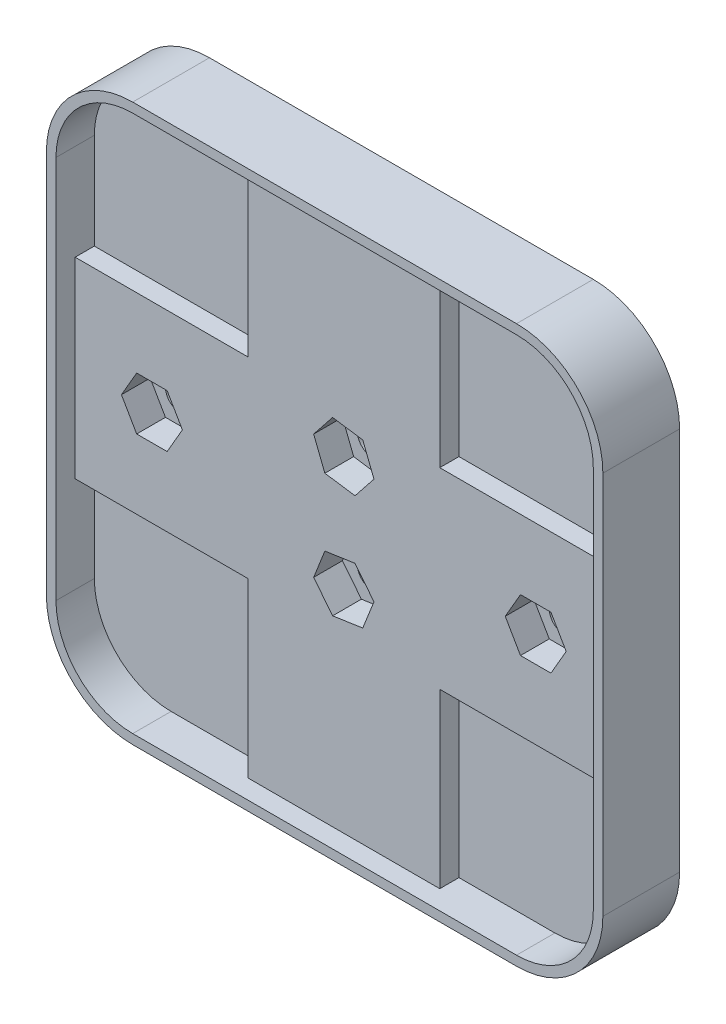
SolidWorks part; units mm, degrees
ref_plane "Front" through (0, 0, 0) normal (0, 0, 1) x (1, 0, 0)
ref_plane "Top" through (0, 0, 0) normal (0, 1, 0) x (1, 0, 0)
ref_plane "Right" through (0, 0, 0) normal (1, 0, 0) x (0, 0, -1)
sketch "草图1" plane through (0, 0, 0) normal (0, 0, 1) x (1, 0, 0)
  line L0 (-15.4063, 105.3183) -> (-15.4063, -125.7754) construction
  line L1 (-238.6458, 35.5371) -> (237.4375, 35.5371) construction
  line L2 (-35.4063, 64.5371) -> (4.5937, 64.5371)
  line L3 (13.5937, 55.5371) -> (13.5937, 15.5371)
  line L4 (4.5937, 6.5371) -> (-35.4063, 6.5371)
  line L5 (-44.4063, 15.5371) -> (-44.4063, 55.5371)
  arc A0 (13.5937, 55.5371) -> (4.5937, 64.5371) centre (4.5937, 55.5371) ccw
  arc A1 (4.5937, 6.5371) -> (13.5937, 15.5371) centre (4.5937, 15.5371) ccw
  arc A2 (-35.4063, 6.5371) -> (-44.4063, 15.5371) centre (-35.4063, 15.5371) cw
  arc A3 (-44.4063, 55.5371) -> (-35.4063, 64.5371) centre (-35.4063, 55.5371) cw
  point P16 (-44.4063, 64.5371)
  dimension "D5" = 9
  dimension "D6" = 9
  dimension "D1" = 29
  dimension "D2" = 58
  dimension "D3" = 58
  dimension "D4" = 29
extrude "凸台-拉伸1" add sketch "草图1" against normal blind 4
sketch "草图2" plane through (0, 0, 0) normal (0, 0, 1) x (1, 0, 0)
  line L0 (13.5937, 15.5371) -> (13.5937, 55.5371) construction
  line L1 (-35.4063, 6.5371) -> (4.5937, 6.5371) construction
  line L2 (-44.4063, 55.5371) -> (-44.4063, 15.5371) construction
  line L3 (4.5937, 64.5371) -> (-35.4063, 64.5371) construction
  line L4 (13.5937, 15.5371) -> (13.5937, 55.5371)
  line L5 (-35.4063, 6.5371) -> (4.5937, 6.5371)
  line L6 (-44.4063, 55.5371) -> (-44.4063, 15.5371)
  line L7 (4.5937, 64.5371) -> (-35.4063, 64.5371)
  line L8 (-35.4063, 63.5371) -> (-25.4063, 63.5371)
  line L9 (12.5937, 55.5371) -> (12.5937, 45.5371)
  line L10 (-43.4063, 55.5371) -> (-43.4063, 45.5371)
  line L11 (-35.4063, 7.5371) -> (-25.4063, 7.5371)
  line L12 (-25.4063, 63.5371) -> (-25.4063, 45.5371)
  line L13 (-15.4063, 63.5371) -> (-15.4063, 7.5371) construction
  line L14 (-44.4063, 35.5371) -> (13.5937, 35.5371) construction
  line L15 (-5.4063, 63.5371) -> (-5.4063, 45.5371)
  line L16 (-25.4063, 45.5371) -> (-43.4063, 45.5371)
  line L17 (-5.4063, 45.5371) -> (12.5937, 45.5371)
  line L18 (-5.4063, 25.5371) -> (12.5937, 25.5371)
  line L19 (-25.4063, 25.5371) -> (-43.4063, 25.5371)
  line L20 (-25.4063, 25.5371) -> (-25.4063, 7.5371)
  line L21 (-5.4063, 25.5371) -> (-5.4063, 7.5371)
  line L22 (-43.4063, 25.5371) -> (-43.4063, 15.5371)
  line L23 (-5.4063, 7.5371) -> (4.5937, 7.5371)
  line L24 (12.5937, 25.5371) -> (12.5937, 15.5371)
  line L25 (-5.4063, 63.5371) -> (4.5937, 63.5371)
  arc A0 (13.5937, 55.5371) -> (4.5937, 64.5371) centre (4.5937, 55.5371) ccw construction
  arc A1 (4.5937, 6.5371) -> (13.5937, 15.5371) centre (4.5937, 15.5371) ccw construction
  arc A2 (-44.4063, 15.5371) -> (-35.4063, 6.5371) centre (-35.4063, 15.5371) ccw construction
  arc A3 (-35.4063, 64.5371) -> (-44.4063, 55.5371) centre (-35.4063, 55.5371) ccw construction
  arc A4 (13.5937, 55.5371) -> (4.5937, 64.5371) centre (4.5937, 55.5371) ccw
  arc A5 (4.5937, 6.5371) -> (13.5937, 15.5371) centre (4.5937, 15.5371) ccw
  arc A6 (-44.4063, 15.5371) -> (-35.4063, 6.5371) centre (-35.4063, 15.5371) ccw
  arc A7 (-35.4063, 64.5371) -> (-44.4063, 55.5371) centre (-35.4063, 55.5371) ccw
  arc A8 (-35.4063, 7.5371) -> (-43.4063, 15.5371) centre (-35.4063, 15.5371) cw
  arc A9 (4.5937, 7.5371) -> (12.5937, 15.5371) centre (4.5937, 15.5371) ccw
  arc A10 (12.5937, 55.5371) -> (4.5937, 63.5371) centre (4.5937, 55.5371) ccw
  arc A11 (-43.4063, 55.5371) -> (-35.4063, 63.5371) centre (-35.4063, 55.5371) cw
  dimension "D5" = 8
  dimension "D1" = 1
  dimension "D2" = 1
  dimension "D3" = 1
  dimension "D4" = 1
  dimension "D6" = 10
  dimension "D7" = 10
  dimension "D8" = 10
extrude "凸台-拉伸2" add sketch "草图2" along normal blind 2
sketch "草图3" plane through (0, 0, 2) normal (0, 0, 1) x (1, 0, 0)
  line L0 (-43.4063, 55.5371) -> (-43.4063, 45.5371) construction
  line L1 (-43.4063, 25.5371) -> (-43.4063, 15.5371) construction
  line L2 (-35.4063, 7.5371) -> (-25.4063, 7.5371) construction
  line L3 (-5.4063, 7.5371) -> (4.5937, 7.5371) construction
  line L4 (12.5937, 15.5371) -> (12.5937, 25.5371) construction
  line L5 (12.5937, 45.5371) -> (12.5937, 55.5371) construction
  line L6 (4.5937, 63.5371) -> (-5.4063, 63.5371) construction
  line L7 (-25.4063, 63.5371) -> (-35.4063, 63.5371) construction
  line L8 (13.5937, 15.5371) -> (13.5937, 55.5371) construction
  line L9 (-35.4063, 6.5371) -> (4.5937, 6.5371) construction
  line L10 (-44.4063, 55.5371) -> (-44.4063, 15.5371) construction
  line L11 (4.5937, 64.5371) -> (-35.4063, 64.5371) construction
  line L12 (-43.4063, 55.5371) -> (-43.4063, 45.5371)
  line L13 (-43.4063, 25.5371) -> (-43.4063, 15.5371)
  line L14 (-35.4063, 7.5371) -> (-25.4063, 7.5371)
  line L15 (-5.4063, 7.5371) -> (4.5937, 7.5371)
  line L16 (12.5937, 15.5371) -> (12.5937, 25.5371)
  line L17 (12.5937, 45.5371) -> (12.5937, 55.5371)
  line L18 (4.5937, 63.5371) -> (-5.4063, 63.5371)
  line L19 (-25.4063, 63.5371) -> (-35.4063, 63.5371)
  line L20 (13.5937, 15.5371) -> (13.5937, 55.5371)
  line L21 (-35.4063, 6.5371) -> (4.5937, 6.5371)
  line L22 (-44.4063, 55.5371) -> (-44.4063, 15.5371)
  line L23 (4.5937, 64.5371) -> (-35.4063, 64.5371)
  line L24 (-25.4063, 63.5371) -> (-5.4063, 63.5371)
  line L25 (12.5937, 45.5371) -> (12.5937, 25.5371)
  line L26 (-5.4063, 7.5371) -> (-25.4063, 7.5371)
  line L27 (-43.4063, 45.5371) -> (-43.4063, 25.5371)
  arc A0 (-43.4063, 15.5371) -> (-35.4063, 7.5371) centre (-35.4063, 15.5371) ccw construction
  arc A1 (4.5937, 7.5371) -> (12.5937, 15.5371) centre (4.5937, 15.5371) ccw construction
  arc A2 (12.5937, 55.5371) -> (4.5937, 63.5371) centre (4.5937, 55.5371) ccw construction
  arc A3 (-35.4063, 63.5371) -> (-43.4063, 55.5371) centre (-35.4063, 55.5371) ccw construction
  arc A4 (13.5937, 55.5371) -> (4.5937, 64.5371) centre (4.5937, 55.5371) ccw construction
  arc A5 (4.5937, 6.5371) -> (13.5937, 15.5371) centre (4.5937, 15.5371) ccw construction
  arc A6 (-44.4063, 15.5371) -> (-35.4063, 6.5371) centre (-35.4063, 15.5371) ccw construction
  arc A7 (-35.4063, 64.5371) -> (-44.4063, 55.5371) centre (-35.4063, 55.5371) ccw construction
  arc A8 (-43.4063, 15.5371) -> (-35.4063, 7.5371) centre (-35.4063, 15.5371) ccw
  arc A9 (4.5937, 7.5371) -> (12.5937, 15.5371) centre (4.5937, 15.5371) ccw
  arc A10 (12.5937, 55.5371) -> (4.5937, 63.5371) centre (4.5937, 55.5371) ccw
  arc A11 (-35.4063, 63.5371) -> (-43.4063, 55.5371) centre (-35.4063, 55.5371) ccw
  arc A12 (13.5937, 55.5371) -> (4.5937, 64.5371) centre (4.5937, 55.5371) ccw
  arc A13 (4.5937, 6.5371) -> (13.5937, 15.5371) centre (4.5937, 15.5371) ccw
  arc A14 (-44.4063, 15.5371) -> (-35.4063, 6.5371) centre (-35.4063, 15.5371) ccw
  arc A15 (-35.4063, 64.5371) -> (-44.4063, 55.5371) centre (-35.4063, 55.5371) ccw
extrude "凸台-拉伸3" add sketch "草图3" along normal blind 2
sketch "草图4" plane through (0, 0, 2) normal (0, 0, 1) x (1, 0, 0)
  line L0 (-15.4063, 63.5371) -> (-15.4063, 7.5371) construction
  line L1 (-5.4063, 63.5371) -> (-25.4063, 63.5371) construction
  line L2 (-35.4063, 7.5371) -> (4.5937, 7.5371) construction
  line L3 (-43.4063, 35.5371) -> (12.5937, 35.5371) construction
  line L4 (-43.4063, 45.5371) -> (-43.4063, 25.5371) construction
  line L5 (12.5937, 25.5371) -> (12.5937, 45.5371) construction
  circle A0 centre (-15.4063, 41.5371) radius 1.6
  circle A1 centre (-15.4063, 29.5371) radius 1.6
  circle A2 centre (4.5937, 35.5371) radius 1.6
  circle A3 centre (-35.4063, 35.5371) radius 1.6
  dimension "D4" = 3.2
  dimension "D5" = 3.2
  dimension "D6" = 3.2
  dimension "D7" = 3.2
  dimension "D8" = 20
  dimension "D1" = 12
  dimension "D2" = 40
  dimension "D3" = 6
extrude "切除-拉伸1" cut sketch "草图4" against normal blind 10
sketch "草图5" plane through (0, 0, 2) normal (0, 0, 1) x (1, 0, 0)
  line L1 (-13.4319, 44.0241) -> (-16.5729, 44.4904)
  line L2 (-16.5729, 44.4904) -> (-18.5473, 42.0034)
  line L3 (-18.5473, 42.0034) -> (-17.3806, 39.0501)
  line L4 (-17.3806, 39.0501) -> (-14.2396, 38.5837)
  line L5 (-14.2396, 38.5837) -> (-12.2652, 41.0708)
  line L6 (-12.2652, 41.0708) -> (-13.4319, 44.0241)
  line L7 (1.4183, 35.5371) -> (3.006, 32.7871)
  line L8 (3.006, 32.7871) -> (6.1815, 32.7871)
  line L9 (6.1815, 32.7871) -> (7.7692, 35.5371)
  line L10 (7.7692, 35.5371) -> (6.1815, 38.2871)
  line L11 (6.1815, 38.2871) -> (3.006, 38.2871)
  line L12 (3.006, 38.2871) -> (1.4183, 35.5371)
  line L13 (-13.4319, 27.0501) -> (-12.2652, 30.0034)
  line L14 (-12.2652, 30.0034) -> (-14.2396, 32.4904)
  line L15 (-14.2396, 32.4904) -> (-17.3806, 32.0241)
  line L16 (-17.3806, 32.0241) -> (-18.5473, 29.0708)
  line L17 (-18.5473, 29.0708) -> (-16.5729, 26.5837)
  line L18 (-16.5729, 26.5837) -> (-13.4319, 27.0501)
  line L19 (-32.2308, 35.5371) -> (-33.8185, 38.2871)
  line L20 (-33.8185, 38.2871) -> (-36.994, 38.2871)
  line L21 (-36.994, 38.2871) -> (-38.5817, 35.5371)
  line L22 (-38.5817, 35.5371) -> (-36.994, 32.7871)
  line L23 (-36.994, 32.7871) -> (-33.8185, 32.7871)
  line L24 (-33.8185, 32.7871) -> (-32.2308, 35.5371)
  circle A0 centre (-15.4063, 41.5371) radius 2.75 construction
  circle A1 centre (4.5937, 35.5371) radius 2.75 construction
  circle A2 centre (-15.4063, 29.5371) radius 2.75 construction
  circle A3 centre (-35.4063, 35.5371) radius 2.75 construction
  dimension "D1" = 5.5
  dimension "D2" = 5.5
  dimension "D3" = 5.5
  dimension "D4" = 5.5
extrude "切除-拉伸2" cut sketch "草图5" against normal blind 3
